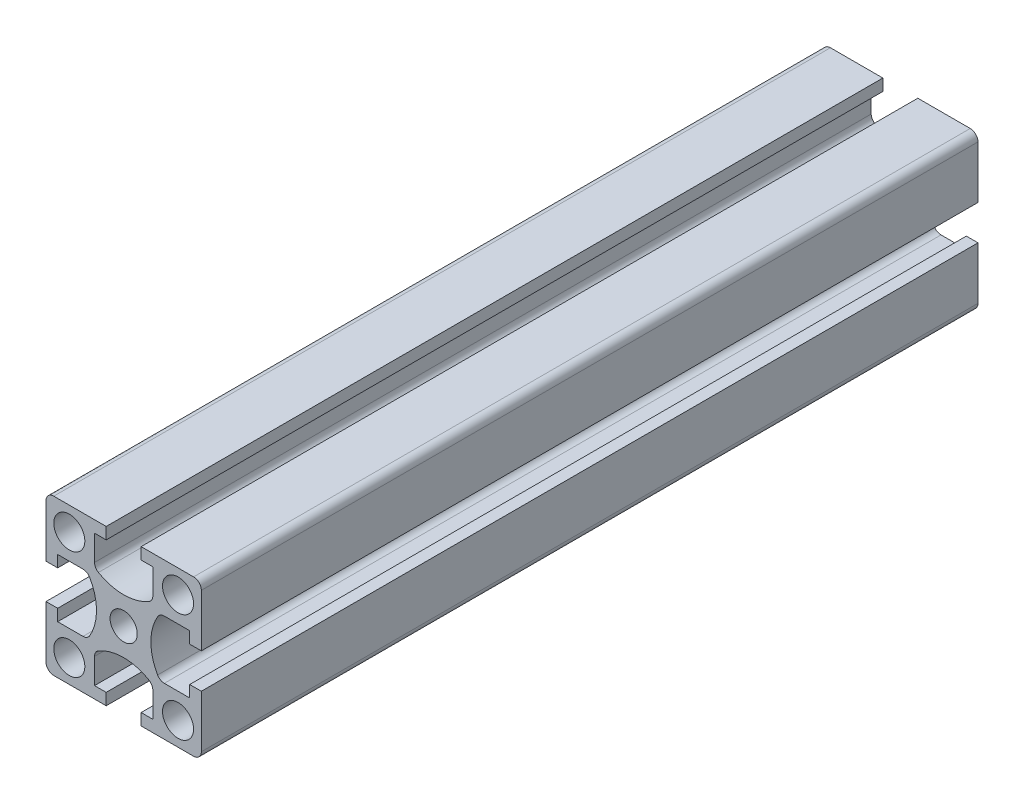
SolidWorks part; units mm, degrees
ref_plane "Front Plane" through (0, 0, 0) normal (0, 0, 1) x (1, 0, 0)
ref_plane "Top Plane" through (0, 0, 0) normal (0, 1, 0) x (1, 0, 0)
ref_plane "Right Plane" through (0, 0, 0) normal (1, 0, 0) x (0, 0, -1)
sketch "Sketch1" plane through (0, 0, 0) normal (0, 0, 1) x (1, 0, 0)
  line L64 (-10, 9) -> (-10, 2.25)
  line L65 (-10, 2.25) -> (-8.5, 2.25)
  line L66 (-8.5, 2.25) -> (-8.5, 3.75)
  line L67 (-8.5, 3.75) -> (-5.2369, 3.75)
  line L68 (-5.2369, -3.75) -> (-8.5, -3.75)
  line L69 (-8.5, -3.75) -> (-8.5, -2.25)
  line L70 (-8.5, -2.25) -> (-10, -2.25)
  line L71 (-10, -2.25) -> (-10, -9)
  line L72 (-9, -10) -> (-2.25, -10)
  line L73 (-2.25, -10) -> (-2.25, -8.5)
  line L74 (-2.25, -8.5) -> (-3.75, -8.5)
  line L75 (-3.75, -8.5) -> (-3.75, -5.2369)
  line L76 (3.75, -5.2369) -> (3.75, -8.5)
  line L77 (3.75, -8.5) -> (2.25, -8.5)
  line L78 (2.25, -8.5) -> (2.25, -10)
  line L79 (2.25, -10) -> (9, -10)
  line L80 (10, -9) -> (10, -2.25)
  line L81 (10, -2.25) -> (8.5, -2.25)
  line L82 (8.5, -2.25) -> (8.5, -3.75)
  line L83 (8.5, -3.75) -> (5.2369, -3.75)
  line L84 (5.2369, 3.75) -> (8.5, 3.75)
  line L85 (8.5, 3.75) -> (8.5, 2.25)
  line L86 (8.5, 2.25) -> (10, 2.25)
  line L87 (10, 2.25) -> (10, 9)
  line L88 (9, 10) -> (2.25, 10)
  line L89 (2.25, 10) -> (2.25, 8.5)
  line L90 (2.25, 8.5) -> (3.75, 8.5)
  line L91 (3.75, 8.5) -> (3.75, 5.2369)
  line L92 (-3.75, 5.2369) -> (-3.75, 8.5)
  line L93 (-3.75, 8.5) -> (-2.25, 8.5)
  line L94 (-2.25, 8.5) -> (-2.25, 10)
  line L95 (-2.25, 10) -> (-9, 10)
  circle A5 centre (-7, -7) radius 2
  circle A6 centre (7, -7) radius 2
  circle A7 centre (7, 7) radius 2
  circle A8 centre (0, 0) radius 1.75
  circle A9 centre (-7, 7) radius 2
  arc A32 (-9, 10) -> (-10, 9) centre (-9, 9) ccw
  arc A33 (-4.3708, 3.25) -> (-5.2369, 3.75) centre (-5.2369, 2.75) ccw
  arc A34 (-4.3708, -3.25) -> (-4.3708, 3.25) centre (-10, 0) ccw
  arc A35 (-5.2369, -3.75) -> (-4.3708, -3.25) centre (-5.2369, -2.75) ccw
  arc A36 (-10, -9) -> (-9, -10) centre (-9, -9) ccw
  arc A37 (-3.25, -4.3708) -> (-3.75, -5.2369) centre (-2.75, -5.2369) ccw
  arc A38 (3.25, -4.3708) -> (-3.25, -4.3708) centre (0, -10) ccw
  arc A39 (3.75, -5.2369) -> (3.25, -4.3708) centre (2.75, -5.2369) ccw
  arc A40 (9, -10) -> (10, -9) centre (9, -9) ccw
  arc A41 (4.3708, -3.25) -> (5.2369, -3.75) centre (5.2369, -2.75) ccw
  arc A42 (4.3708, 3.25) -> (4.3708, -3.25) centre (10, 0) ccw
  arc A43 (5.2369, 3.75) -> (4.3708, 3.25) centre (5.2369, 2.75) ccw
  arc A44 (10, 9) -> (9, 10) centre (9, 9) ccw
  arc A45 (3.25, 4.3708) -> (3.75, 5.2369) centre (2.75, 5.2369) ccw
  arc A46 (-3.25, 4.3708) -> (3.25, 4.3708) centre (0, 10) ccw
  arc A47 (-3.75, 5.2369) -> (-3.25, 4.3708) centre (-2.75, 5.2369) ccw
extrude "Boss-Extrude1" add sketch "Sketch1" along normal blind 100
